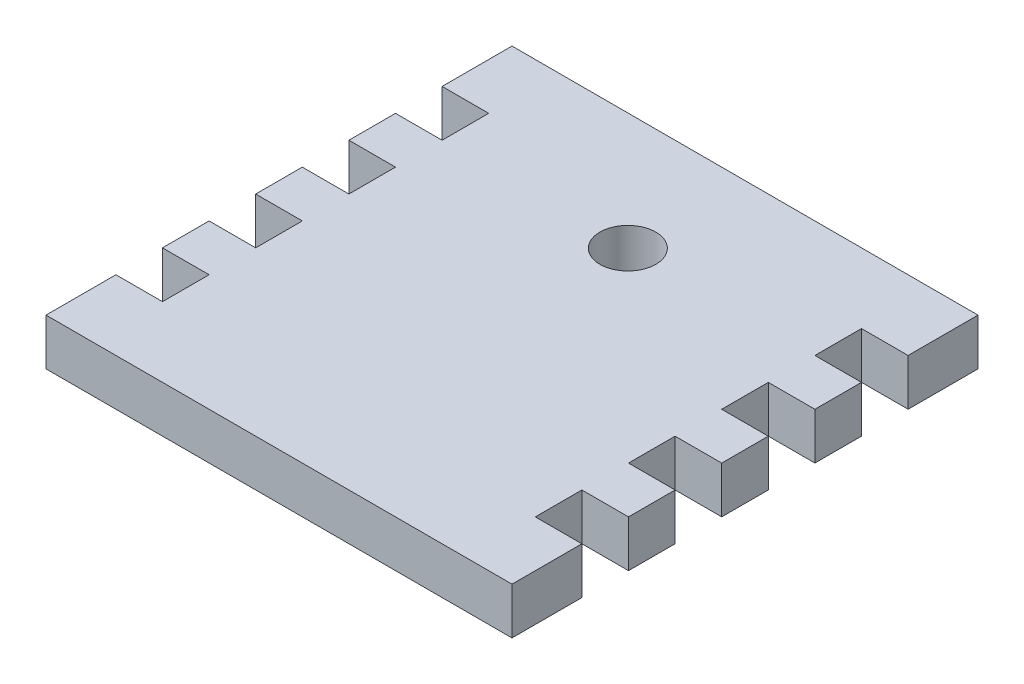
SolidWorks part; units mm, degrees
ref_plane "Front Plane" through (0, 0, 0) normal (0, 0, 1) x (1, 0, 0)
ref_plane "Top Plane" through (0, 0, 0) normal (0, 1, 0) x (1, 0, 0)
ref_plane "Right Plane" through (0, 0, 0) normal (1, 0, 0) x (0, 0, -1)
sketch "Sketch1" plane through (0, 0, 0) normal (0, 1, 0) x (1, 0, 0)
  line L1 (-16.0109, 17.8887) -> (34.7891, 17.8887)
  line L2 (-16.0109, 17.8887) -> (-16.0109, -32.9113)
  line L3 (-16.0109, -32.9113) -> (34.7891, -32.9113)
  line L4 (34.7891, 17.8887) -> (34.7891, -32.9113)
  dimension "D1" = 50.8
  dimension "D2" = 50.8
extrude "Boss-Extrude1" add sketch "Sketch1" along normal blind 5.08
sketch "Sketch2" plane through (0, 5.08, 0) normal (0, 1, 0) x (1, 0, 0)
  line L0 (9.3891, 17.8887) -> (9.3891, -32.9113) construction
  line L1 (34.7891, 17.8887) -> (-16.0109, 17.8887) construction
  line L2 (-16.0109, -32.9113) -> (34.7891, -32.9113) construction
  line L3 (-16.0109, -7.5113) -> (34.7891, -7.5113) construction
  line L4 (-16.0109, 17.8887) -> (-16.0109, -32.9113) construction
  line L5 (34.7891, -32.9113) -> (34.7891, 17.8887) construction
  line L6 (29.7091, -20.2113) -> (29.7091, -25.2913)
  line L7 (-16.0109, -10.0513) -> (-10.9309, -10.0513)
  line L8 (-16.0109, -10.0513) -> (-16.0109, -15.1313)
  line L9 (-16.0109, -15.1313) -> (-10.9309, -15.1313)
  line L10 (-10.9309, -10.0513) -> (-10.9309, -15.1313)
  line L11 (-16.0109, -20.2113) -> (-10.9309, -20.2113)
  line L12 (-16.0109, -20.2113) -> (-16.0109, -25.2913)
  line L13 (-16.0109, -25.2913) -> (-10.9309, -25.2913)
  line L14 (-10.9309, -20.2113) -> (-10.9309, -25.2913)
  line L15 (34.7891, -25.2913) -> (29.7091, -25.2913)
  line L16 (34.7891, -20.2113) -> (34.7891, -25.2913)
  line L17 (34.7891, -20.2113) -> (29.7091, -20.2113)
  line L18 (29.7091, -10.0513) -> (29.7091, -15.1313)
  line L19 (34.7891, -15.1313) -> (29.7091, -15.1313)
  line L20 (34.7891, -10.0513) -> (34.7891, -15.1313)
  line L21 (34.7891, -10.0513) -> (29.7091, -10.0513)
  line L22 (34.7891, -4.9713) -> (29.7091, -4.9713)
  line L23 (34.7891, -4.9713) -> (34.7891, 0.1087)
  line L24 (34.7891, 0.1087) -> (29.7091, 0.1087)
  line L25 (29.7091, -4.9713) -> (29.7091, 0.1087)
  line L26 (34.7891, 5.1887) -> (29.7091, 5.1887)
  line L27 (34.7891, 5.1887) -> (34.7891, 10.2687)
  line L28 (34.7891, 10.2687) -> (29.7091, 10.2687)
  line L29 (-10.9309, 5.1887) -> (-10.9309, 10.2687)
  line L30 (-16.0109, 10.2687) -> (-10.9309, 10.2687)
  line L31 (-16.0109, 5.1887) -> (-16.0109, 10.2687)
  line L32 (-16.0109, 5.1887) -> (-10.9309, 5.1887)
  line L33 (-10.9309, -4.9713) -> (-10.9309, 0.1087)
  line L34 (-16.0109, 0.1087) -> (-10.9309, 0.1087)
  line L35 (-16.0109, -4.9713) -> (-16.0109, 0.1087)
  line L36 (-16.0109, -4.9713) -> (-10.9309, -4.9713)
  line L37 (29.7091, 5.1887) -> (29.7091, 10.2687)
  circle A0 centre (9.3891, 5.1201) radius 3.048
  dimension "D1" = 6.096
  dimension "D2" = 2.54
  dimension "D3" = 5.08
  dimension "D4" = 5.08
  dimension "D5" = 5.08
  dimension "D6" = 5.08
  dimension "D7" = 5.08
  dimension "D8" = 38.0314
extrude "Cut-Extrude1" cut sketch "Sketch2" against normal blind 5.08
